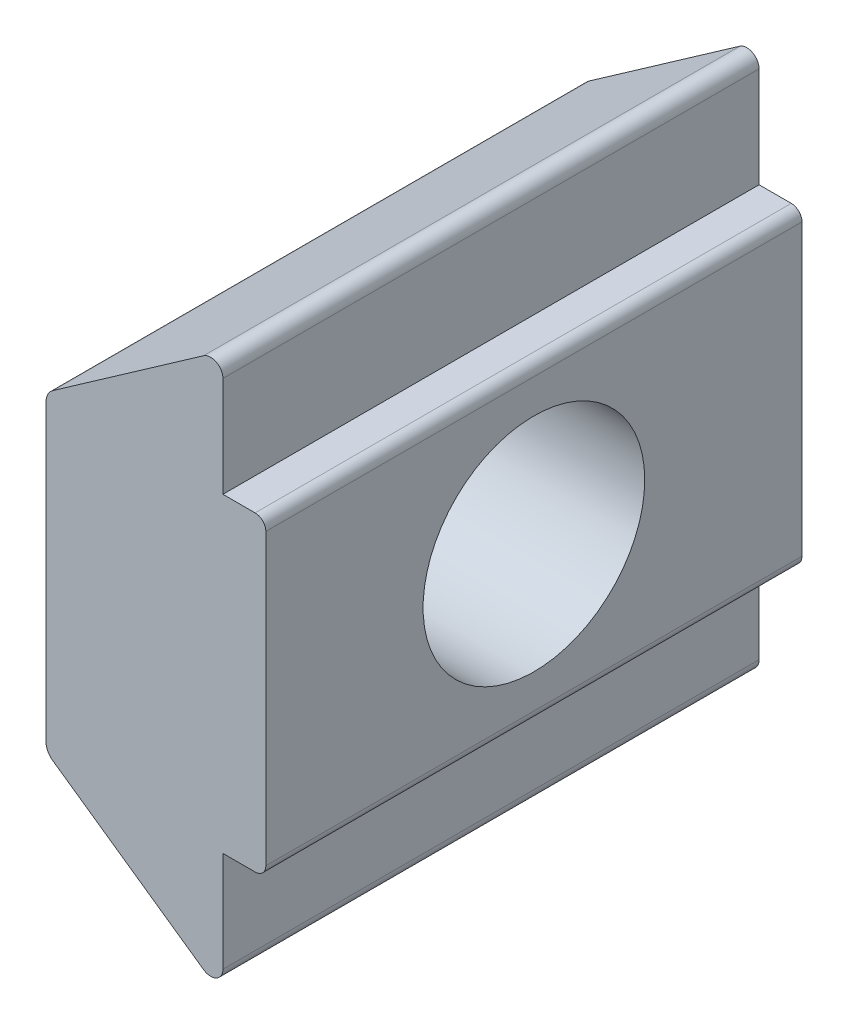
SolidWorks part; units mm, degrees
ref_plane "Front Plane" through (0, 0, 0) normal (0, 0, 1) x (1, 0, 0)
ref_plane "Top Plane" through (0, 0, 0) normal (0, 1, 0) x (1, 0, 0)
ref_plane "Right Plane" through (0, 0, 0) normal (1, 0, 0) x (0, 0, -1)
sketch "Sketch1" plane through (0, 0, 0) normal (0, 0, 1) x (1, 0, 0)
  line L0 (-4.1, 2.7438) -> (-4.1, -2.7438)
  line L1 (-3.9721, -2.9896) -> (-1.16, -4.9586)
  line L2 (-0.8, -4.7712) -> (-0.8, -2.9)
  line L3 (-0.8, -2.9) -> (-0.2, -2.9)
  line L4 (0, -2.7) -> (0, 2.7)
  line L5 (-0.2, 2.9) -> (-0.8, 2.9)
  line L6 (-0.8, 2.9) -> (-0.8, 4.7712)
  line L7 (-1.16, 4.9586) -> (-3.9721, 2.9896)
  line L8 (0, 0) -> (-4.1, 0) construction
  line L9 (2.255, 0) -> (-2.255, 0) construction
  line L10 (0, -5.5) -> (0, 5.5) construction
  line L11 (-4.1, 5) -> (-0.8, 5) construction
  arc A0 (-4.1, -2.7438) -> (-3.9721, -2.9896) centre (-3.8, -2.7438) ccw
  arc A1 (-1.16, -4.9586) -> (-0.8, -4.7712) centre (-1.0288, -4.7712) ccw
  arc A2 (-0.2, -2.9) -> (0, -2.7) centre (-0.2, -2.7) ccw
  arc A3 (0, 2.7) -> (-0.2, 2.9) centre (-0.2, 2.7) ccw
  arc A4 (-0.8, 4.7712) -> (-1.16, 4.9586) centre (-1.0288, 4.7712) ccw
  arc A5 (-3.9721, 2.9896) -> (-4.1, 2.7438) centre (-3.8, 2.7438) ccw
  point P26 (-4.1, 2.9)
  dimension "FIX_6" = 0.2
  dimension "FIX_7" = 0.3
  dimension "FIX_1" = 5.8
  dimension "FIX_2" = 0.8
  dimension "FIX_3" = 3.3
  dimension "FIX_4" = 70
  dimension "FIX_5" = 5.8
  dimension "FIX_8" = 10
extrude "Boss-Extrude1" add sketch "Sketch1" along normal mid plane 10
hole_wizard "Tap1" positions "Sketch3" profile "Sketch2" hole size "M5x0.8" standard "JIS" end condition through all
sketch "Sketch3" plane through (0, 0, 0) normal (1, 0, 0) x (0, 0, -1)
  point P0 (0, 0)
sketch "Sketch2" plane through (0, 0, 0) normal (0, 1, 0) x (0, 0, -1)
  line L0 (0, 0) -> (0, 4.1)
  line L1 (0, 4.1) -> (2.067, 4.1)
  line L2 (2.067, 4.1) -> (2.067, 0)
  line L5 (2.067, 0) -> (0, 0)
  line L11 (0, -6.35) -> (0, 107.95) construction
  dimension "Thru Hole Dia." = 4.134
  dimension "Thru Hole Depth" = 4.1
cosmetic thread "Thread1" parameters "HTD"=5
